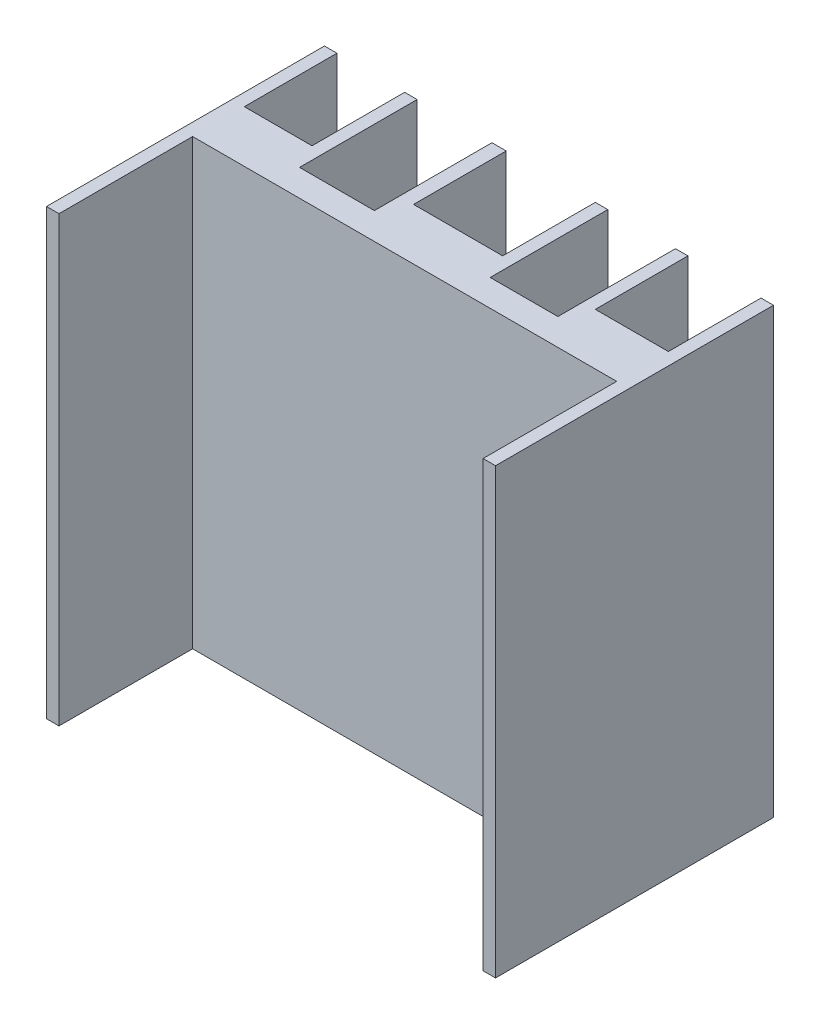
SolidWorks part; units mm, degrees
ref_plane "前视基准面" through (0, 0, 0) normal (0, 0, 1) x (1, 0, 0)
ref_plane "上视基准面" through (0, 0, 0) normal (0, 1, 0) x (1, 0, 0)
ref_plane "右视基准面" through (0, 0, 0) normal (1, 0, 0) x (0, 0, -1)
sketch "草图1" plane through (0, 0, 0) normal (0, 1, 0) x (1, 0, 0)
  line L5 (-2.4, 16.3) -> (2.6, 16.3)
  line L7 (-12.6, 21.5) -> (-12.6, 5.9)
  line L8 (-11.9, 5.9) -> (-12.6, 5.9)
  line L9 (-11.9, 5.9) -> (-11.9, 13.4)
  line L10 (-11.9, 13.4) -> (11.9, 13.4)
  line L11 (11.9, 13.4) -> (11.9, 5.9)
  line L12 (11.9, 5.9) -> (12.6, 5.9)
  line L13 (12.6, 5.9) -> (12.6, 21.5)
  line L14 (-12.6, 21.5) -> (-11.9, 21.5)
  line L15 (-11.9, 21.5) -> (-11.9, 16.3)
  line L16 (-11.9, 16.3) -> (-8.1, 16.3)
  line L17 (-8.1, 16.3) -> (-8.1, 21.5)
  line L18 (-8.1, 21.5) -> (-7.4, 21.5)
  line L19 (-7.4, 21.5) -> (-7.4, 14.9)
  line L20 (-7.4, 14.9) -> (-3.2, 14.9)
  line L21 (-3.2, 14.9) -> (-3.2, 21.5)
  line L22 (-3.2, 21.5) -> (-2.4, 21.5)
  line L23 (-2.4, 21.5) -> (-2.4, 16.3)
  line L24 (2.6, 16.3) -> (2.6, 21.5)
  line L25 (2.6, 21.5) -> (3.3, 21.5)
  line L26 (3.3, 21.5) -> (3.3, 14.9)
  line L27 (3.3, 14.9) -> (7.1, 14.9)
  line L28 (7.1, 14.9) -> (7.1, 21.5)
  line L29 (7.1, 21.5) -> (7.8, 21.5)
  line L30 (7.8, 21.5) -> (7.8, 16.3)
  line L31 (11.9, 16.3) -> (7.8, 16.3)
  line L32 (11.9, 16.3) -> (11.9, 21.5)
  line L33 (11.9, 21.5) -> (12.6, 21.5)
  point P0 (0, 0)
  dimension "D2" = 5
  dimension "D3" = 15.6
  dimension "D4" = 0.7
  dimension "D5" = 7.5
  dimension "D6" = 23.8
  dimension "D7" = 5.2
  dimension "D8" = 3.8
  dimension "D9" = 6.6
  dimension "D10" = 4.2
  dimension "D11" = 3.8
extrude "凸台-拉伸1" add sketch "草图1" along normal blind 24.9
